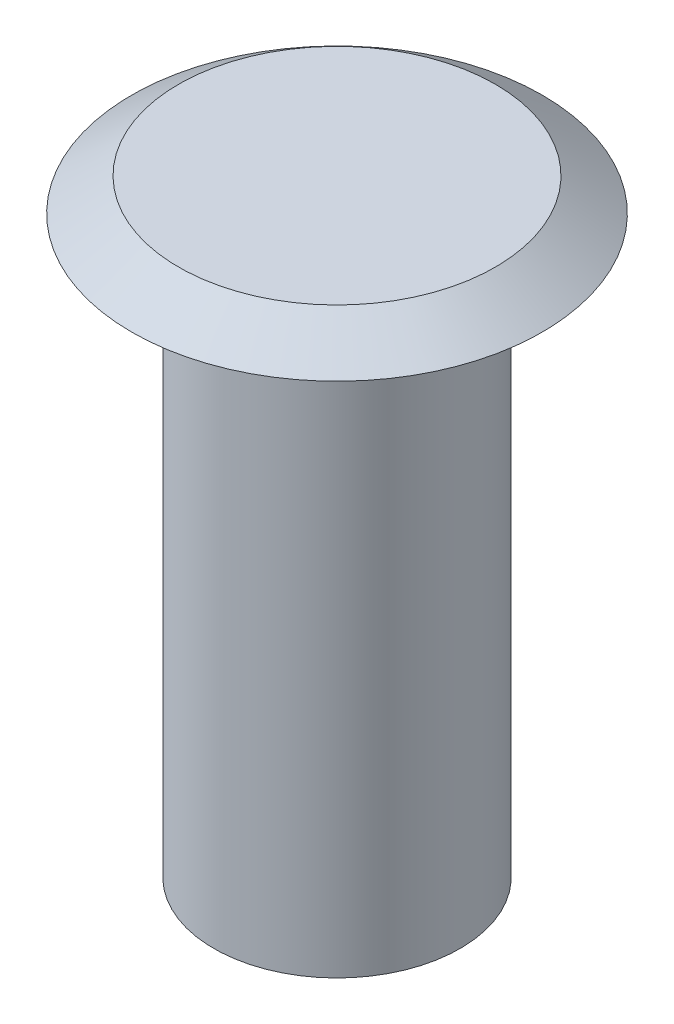
SolidWorks part; units mm, degrees
ref_plane "前视基准面" through (0, 0, 0) normal (0, 0, 1) x (1, 0, 0)
ref_plane "上视基准面" through (0, 0, 0) normal (0, 1, 0) x (1, 0, 0)
ref_plane "右视基准面" through (0, 0, 0) normal (1, 0, 0) x (0, 0, -1)
other "Configuration Table"
sketch "草图1" plane through (0, 0, 0) normal (0, 0, 1) x (1, 0, 0)
  line L0 (0, 0) -> (0, 7.4) construction
  line L1 (0, 7.4) -> (-1.9287, 7.4)
  line L2 (-1.9287, 7.4) -> (-2.5, 7)
  line L3 (-2.5, 7) -> (-1.5, 7)
  line L4 (-1.5, 7) -> (-1.5, 0)
  line L5 (-1.5, 0) -> (-0.6, 0)
  line L6 (-0.6, 0) -> (-0.6, 4)
  line L7 (-0.6, 4) -> (0, 4)
  line L8 (0, 4) -> (0, 7.4)
  dimension "D1" = 1.2
  dimension "D2" = 3
  dimension "D3" = 7
  dimension "D4" = 4
  dimension "D5" = 0.4
  dimension "D6" = 145
  dimension "D7" = 5
revolve "旋转1" add sketch "草图1" angle 360 about L0
